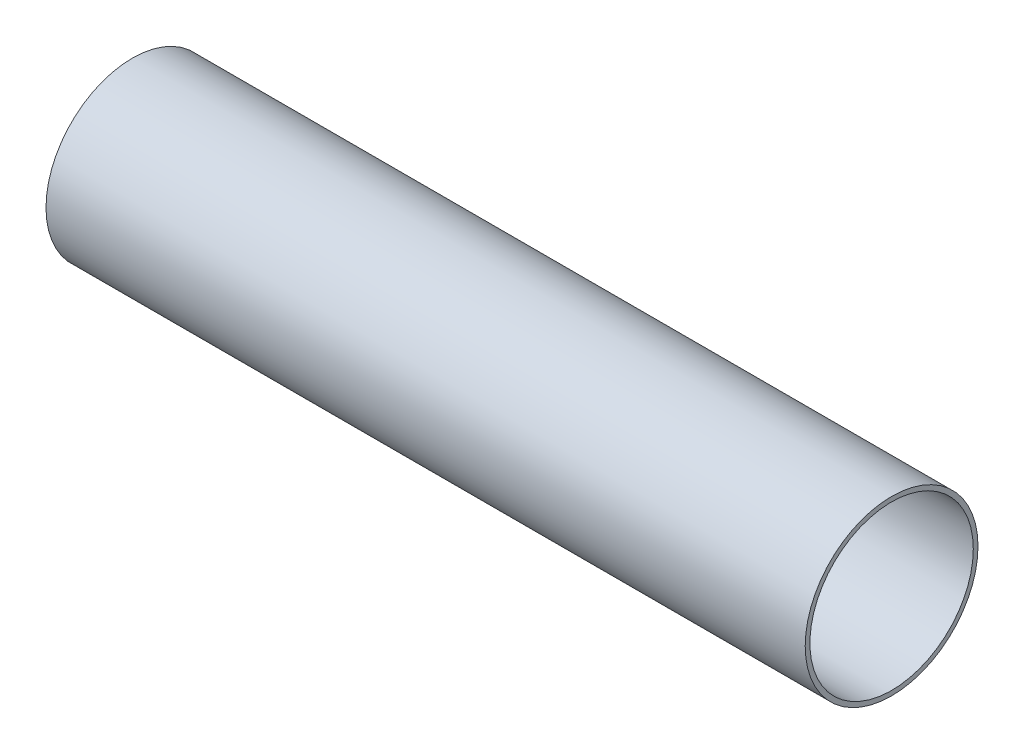
SolidWorks part; units mm, degrees
ref_plane "Front Plane" through (0, 0, 0) normal (1, 0, 0) x (0, 1, 0)
ref_plane "Top Plane" through (0, 0, 0) normal (0, 0, 1) x (0, 1, 0)
ref_plane "Right Plane" through (0, 0, 0) normal (0, 1, 0) x (-1, 0, 0)
sketch "Sketch1" plane through (0, 0, 0) normal (1, 0, 0) x (0, 1, 0)
  circle A0 centre (0, 0) radius 28.9052
  circle A1 centre (0, 0) radius 27.3304
  dimension "D1" = 57.8104
  dimension "D2" = 54.6608
extrude "Boss-Extrude1" add sketch "Sketch1" along normal blind 254
